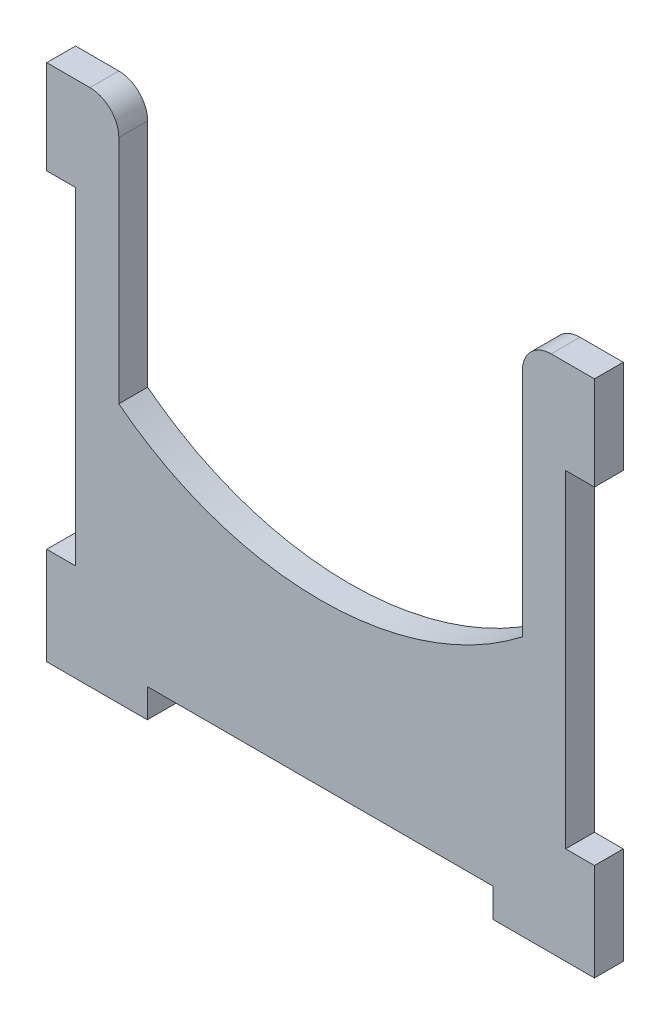
SolidWorks part; units mm, degrees
ref_plane "Ebene vorne" through (0, 0, 0) normal (0, 0, 1) x (1, 0, 0)
ref_plane "Ebene oben" through (0, 0, 0) normal (0, 1, 0) x (1, 0, 0)
ref_plane "Ebene rechts" through (0, 0, 0) normal (1, 0, 0) x (0, 0, -1)
sketch "Skizze1" plane through (0, 0, 0) normal (0, 0, 1) x (1, 0, 0)
  line L0 (-61.3783, 63.8192) -> (-56.3783, 63.8192)
  line L1 (-61.3783, 80.0783) -> (-53.8783, 80.0783)
  line L2 (-61.3783, 80.0783) -> (-61.3783, 63.8192)
  line L3 (-61.3783, -9.9217) -> (-43.9395, -9.9217)
  line L4 (33.6217, 80.0783) -> (33.6217, 63.8192)
  line L5 (26.1217, 80.0783) -> (33.6217, 80.0783)
  line L6 (28.6217, 63.8192) -> (28.6217, 6.9771)
  line L7 (16.0605, -4.9217) -> (-43.9395, -4.9217)
  line L8 (-56.3783, 63.8192) -> (-56.3783, 6.9771)
  line L9 (-48.8783, 35.0783) -> (-48.8783, 75.0783)
  line L10 (21.1217, 35.0783) -> (21.1217, 75.0783)
  line L11 (-56.3783, 6.9771) -> (-61.3783, 6.9771)
  line L12 (28.6217, 6.9771) -> (33.6217, 6.9771)
  line L13 (28.6217, 63.8192) -> (33.6217, 63.8192)
  line L14 (33.6217, 6.9771) -> (33.6217, -9.9217)
  line L15 (-61.3783, 6.9771) -> (-61.3783, -9.9217)
  line L16 (-43.9395, -4.9217) -> (-43.9395, -9.9217)
  line L17 (16.0605, -4.9217) -> (16.0605, -9.9217)
  line L18 (16.0605, -9.9217) -> (33.6217, -9.9217)
  arc A0 (-48.8783, 35.0783) -> (21.1217, 35.0783) centre (-13.8783, 80.12) ccw
  arc A1 (-48.8783, 75.0783) -> (-53.8783, 80.0783) centre (-53.8783, 75.0783) ccw
  arc A2 (26.1217, 80.0783) -> (21.1217, 75.0783) centre (26.1217, 75.0783) ccw
  point P0 (-13.8783, 35.0783)
  point P5 (-13.9395, 35.3982)
  point P6 (-13.8783, 35.0783)
  point P14 (-13.8783, 35.0783)
  point P16 (21.1217, 80.0783)
  dimension "D4" = 77.5
  dimension "D1" = 5
  dimension "D2" = 5
  dimension "D3" = 95
  dimension "D5" = 7.5
  dimension "D6" = 7.5
extrude "Aufsatz-Linear austragen1" add sketch "Skizze1" along normal blind 5
